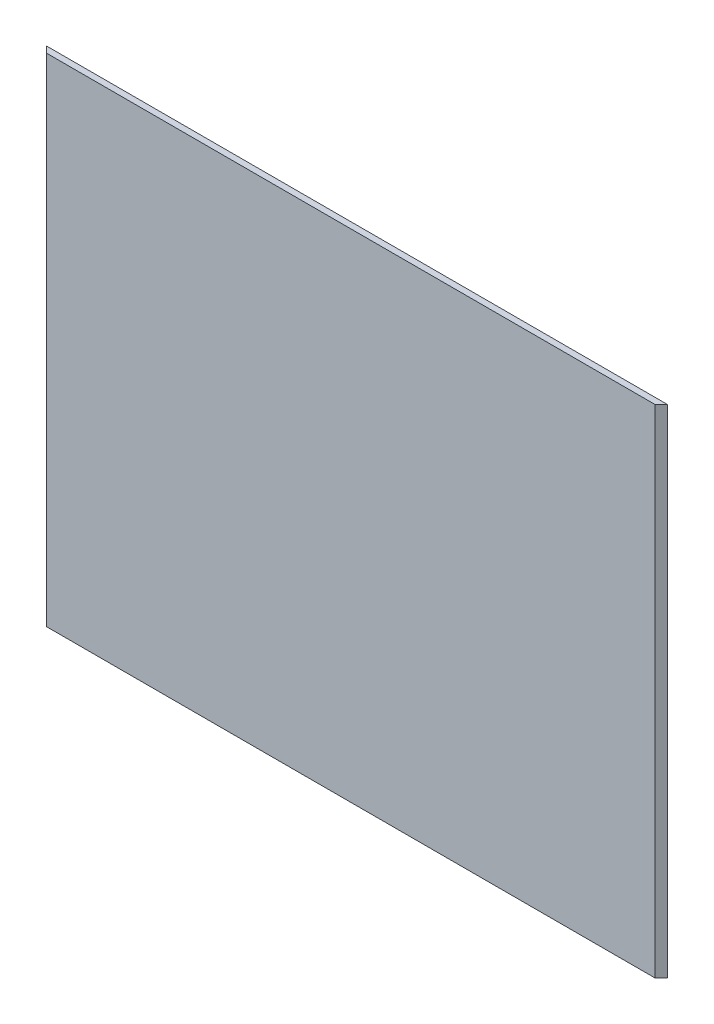
SolidWorks part; units mm, degrees
material "Verre"
ref_plane "Plan de face" through (0, 0, 0) normal (0, 0, 1) x (1, 0, 0)
ref_plane "Plan de dessus" through (0, 0, 0) normal (0, 1, 0) x (1, 0, 0)
ref_plane "Plan de droite" through (0, 0, 0) normal (1, 0, 0) x (0, 0, -1)
sketch "Esquisse1" plane through (0, 0, 0) normal (0, 0, 1) x (1, 0, 0)
  line L1 (250, -200) -> (-250, -200)
  line L2 (250, -200) -> (250, 200)
  line L3 (250, 200) -> (-250, 200)
  line L4 (-250, -200) -> (-250, 200)
  line L5 (250, -200) -> (-250, 200) construction
  line L6 (250, 200) -> (-250, -200) construction
  point P0 (0, 0)
  dimension "D1" = 400
  dimension "D2" = 500
extrude "Boss.-Extru.1" add sketch "Esquisse1" along normal blind 5
sketch "Esquisse2" plane through (0, 200, 0) normal (0, 1, 0) x (1, 0, 0)
  line L0 (-250, -5) -> (-250, 0)
  line L1 (-250, 0) -> (-245, -5)
  line L2 (250, -5) -> (-250, -5) construction
  line L3 (-245, -5) -> (-250, -5)
  line L4 (0, 0) -> (0, -5) construction
  line L5 (250, 0) -> (-250, 0) construction
  line L6 (245, -5) -> (250, -5)
  line L7 (250, 0) -> (245, -5)
  line L8 (250, -5) -> (250, 0)
extrude "Enlèv. mat.-Extru.1" cut sketch "Esquisse2" against normal through all
